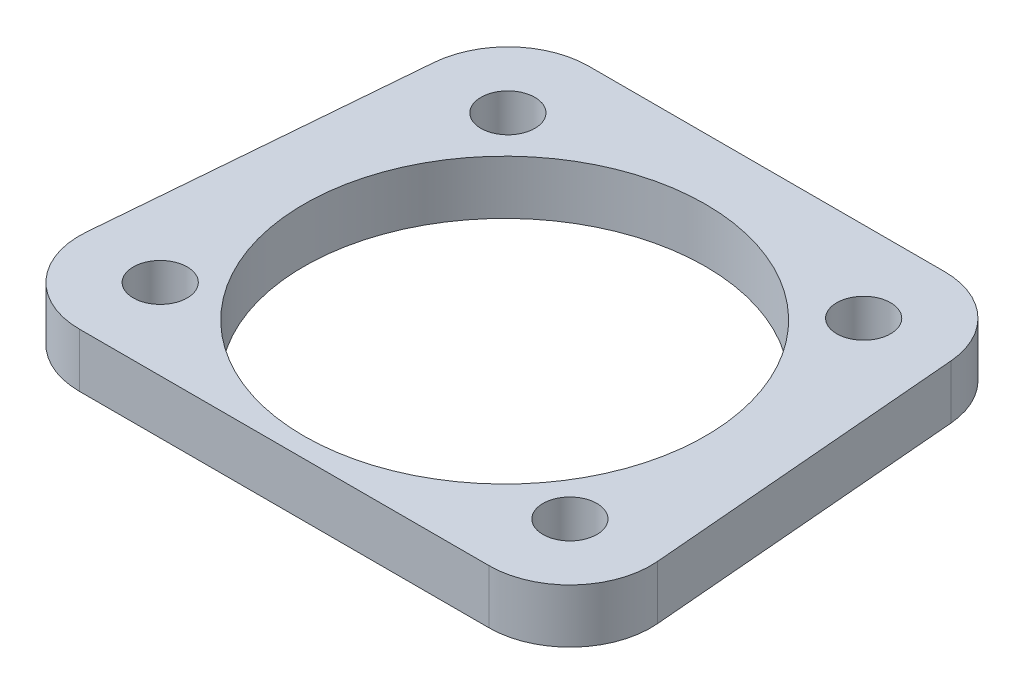
SolidWorks part; units mm, degrees
ref_plane "Front Plane" through (0, 0, 0) normal (0, 0, 1) x (1, 0, 0)
ref_plane "Top Plane" through (0, 0, 0) normal (0, 1, 0) x (1, 0, 0)
ref_plane "Right Plane" through (0, 0, 0) normal (1, 0, 0) x (0, 0, -1)
sketch "Sketch1" plane through (0, 0, 0) normal (0, 1, 0) x (1, 0, 0)
  line L0 (-33, 30.5941) -> (-38, -28.8961) construction
  line L1 (33, 30.5941) -> (38, -28.8961) construction
  line L2 (-33, 30.5941) -> (38, -28.8961) construction
  line L3 (33, 30.5941) -> (-38, -28.8961) construction
  line L4 (-33, 30.5941) -> (33, 30.5941) construction
  line L5 (-33, 30.5941) -> (0, 0) construction
  line L6 (-47.9473, 31.8504) -> (-52.9473, -27.6399)
  line L7 (-38, -43.8961) -> (38, -43.8961)
  line L8 (47.9473, 31.8504) -> (52.9473, -27.6399)
  line L9 (-33, 45.5941) -> (33, 45.5941)
  circle A0 centre (-33, 30.5941) radius 5
  circle A1 centre (33, 30.5941) radius 5
  circle A3 centre (38, -28.8961) radius 5
  circle A4 centre (-38, -28.8961) radius 5
  arc A6 (-33, 45.5941) -> (-47.9473, 31.8504) centre (-33, 30.5941) ccw
  arc A7 (47.9473, 31.8504) -> (33, 45.5941) centre (33, 30.5941) ccw
  arc A8 (38, -43.8961) -> (52.9473, -27.6399) centre (38, -28.8961) ccw
  arc A9 (-52.9473, -27.6399) -> (-38, -43.8961) centre (-38, -28.8961) ccw
  arc A10 (33.5486, 15.6042) -> (34.2563, 15.6468) centre (33, 30.5941) ccw
  circle A11 centre (0, -3) radius 37.25
  point P2 (0, 30.5941)
  point P20 (0, 0)
  dimension "D4" = 10
  dimension "D1" = 59.7
  dimension "D6" = 3
  dimension "D7" = 30
  dimension "D8" = 30
  dimension "D9" = 30
  dimension "D10" = 30
  dimension "D11" = 74.5
  dimension "D2" = 66
  dimension "D3" = 45
  dimension "D5" = 76
extrude "Boss-Extrude1" add sketch "Sketch1" along normal blind 10
